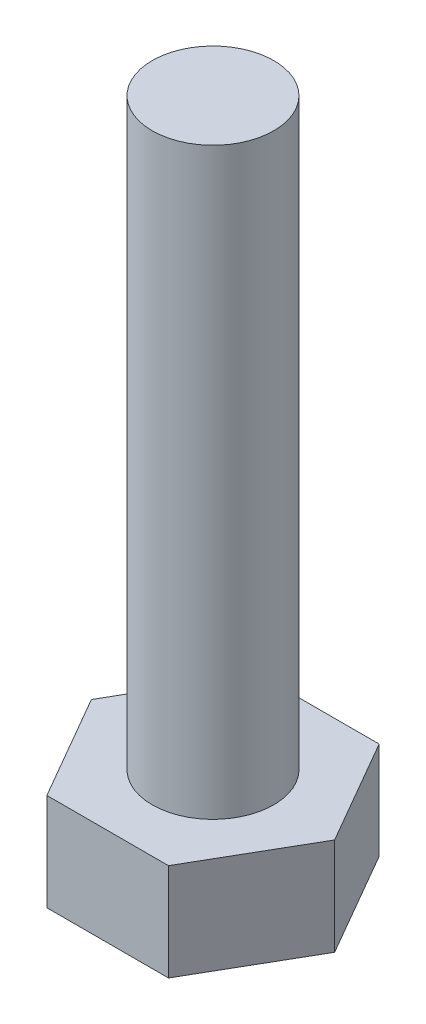
SolidWorks part; units mm, degrees
material "0.6020 (EN-GJL-200)"
ref_plane "前视基准面" through (0, 0, 0) normal (0, 0, 1) x (1, 0, 0)
ref_plane "上视基准面" through (0, 0, 0) normal (0, 1, 0) x (1, 0, 0)
ref_plane "右视基准面" through (0, 0, 0) normal (1, 0, 0) x (0, 0, -1)
other "Configuration Table"
sketch "草图1" plane through (0, 0, 0) normal (0, 1, 0) x (1, 0, 0)
  line L1 (2.5, 0) -> (1.25, 2.1651)
  line L2 (1.25, 2.1651) -> (-1.25, 2.1651)
  line L3 (-1.25, 2.1651) -> (-2.5, 0)
  line L4 (-2.5, 0) -> (-1.25, -2.1651)
  line L5 (-1.25, -2.1651) -> (1.25, -2.1651)
  line L6 (1.25, -2.1651) -> (2.5, 0)
  circle A0 centre (0, 0) radius 2.1651 construction
  dimension "D1" = 2.5
extrude "凸台-拉伸1" add sketch "草图1" along normal blind 2
sketch "草图2" plane through (0, 2, 0) normal (0, 1, 0) x (1, 0, 0)
  circle A0 centre (0, 0) radius 1.25
  dimension "D1" = 2.5
extrude "凸台-拉伸2" add sketch "草图2" along normal blind 12
